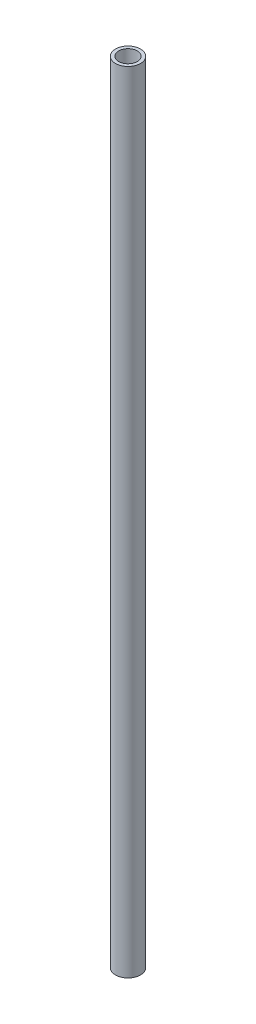
SolidWorks part; units mm, degrees
material "6061 Alloy"
ref_plane "Front Plane" through (0, 0, 0) normal (0, 0, 1) x (1, 0, 0)
ref_plane "Top Plane" through (0, 0, 0) normal (0, 1, 0) x (1, 0, 0)
ref_plane "Right Plane" through (0, 0, 0) normal (1, 0, 0) x (0, 0, -1)
sketch "Sketch1" plane through (0, 0, 0) normal (0, 1, 0) x (1, 0, 0)
  circle A0 centre (0, 0) radius 6.35
  circle A1 centre (0, 0) radius 4.699
  dimension "D1" = 12.7
  dimension "D2" = 1.651
extrude "Boss-Extrude1" add sketch "Sketch1" along normal blind 400.05
